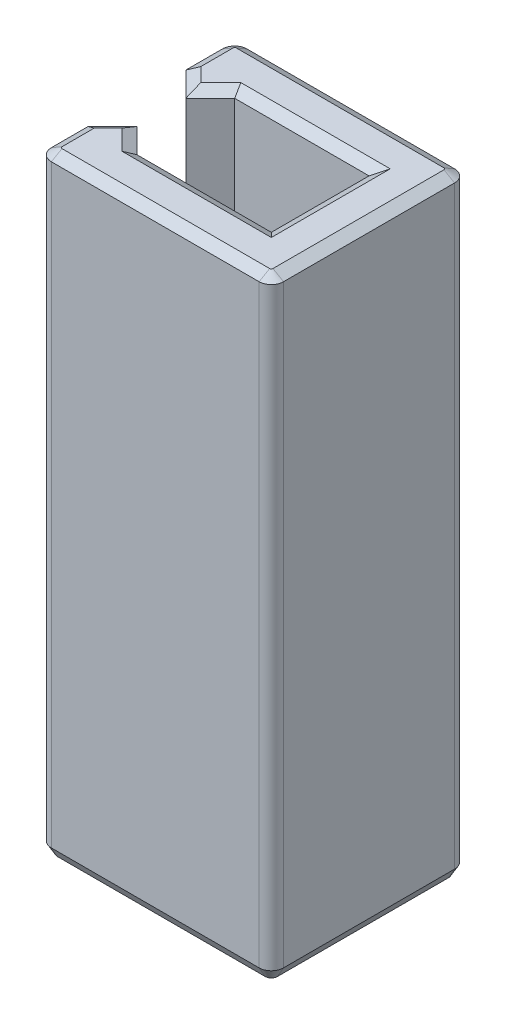
SolidWorks part; units mm, degrees
ref_plane "Alzado" through (0, 0, 0) normal (0, 0, 1) x (1, 0, 0)
ref_plane "Planta" through (0, 0, 0) normal (0, 1, 0) x (1, 0, 0)
ref_plane "Vista lateral" through (0, 0, 0) normal (1, 0, 0) x (0, 0, -1)
sketch "Croquis1" plane through (0, 0, 0) normal (0, 1, 0) x (1, 0, 0)
  line L0 (13.2185, 0) -> (-13.2185, 0) construction
  line L1 (-5.5, 4) -> (-7.5, 2)
  line L2 (8.5, -8) -> (-8.5, -8)
  line L3 (9.5, -7) -> (9.5, 7)
  line L4 (8.5, 8) -> (-8.5, 8)
  line L5 (-9.5, -7) -> (-9.5, -4)
  line L6 (9.5, -8) -> (-9.5, 8) construction
  line L7 (0, -13.2185) -> (0, 13.2185) construction
  line L8 (9.5, 8) -> (-9.5, -8) construction
  line L9 (-5.5, 4) -> (5.5, 4)
  line L10 (-9.5, 4) -> (-9.5, 7)
  line L11 (-5.5, -4) -> (5.5, -4)
  line L12 (5.5, 4) -> (5.5, -4)
  line L14 (-9.5, 4) -> (-7.5, 2)
  line L15 (-13.8316, -10.2338) -> (-13.8316, 16.2032) construction
  line L17 (-7.5, -2) -> (-9.5, -4)
  line L19 (-5.5, -4) -> (-7.5, -2)
  arc A0 (9.5, -7) -> (8.5, -8) centre (8.5, -7) cw
  arc A1 (-9.5, -7) -> (-8.5, -8) centre (-8.5, -7) ccw
  arc A2 (9.5, 7) -> (8.5, 8) centre (8.5, 7) ccw
  arc A3 (-8.5, 8) -> (-9.5, 7) centre (-8.5, 7) ccw
  point P0 (0, 0)
  point P1 (0, 0)
  point P11 (0, 0)
  point P16 (-9.5, 4)
  point P18 (5.5, 4)
  point P20 (-5.5, 4)
  point P27 (-5.5, 4)
  point P28 (-5.5, 4)
  point P29 (-9.5, -4)
  point P30 (-5.5, -4)
  point P31 (-7.5, -2)
  dimension "D11" = 1
  dimension "D1" = 19
  dimension "D2" = 16
  dimension "D3" = 8
  dimension "D4" = 11
  dimension "D5" = 4
  dimension "D6" = 2
  dimension "D7" = 2
  dimension "D8" = 0
  dimension "D9" = 2
  dimension "D10" = 2
extrude "Saliente-Extruir2" add sketch "Croquis1" along normal blind 50
sketch "Croquis3" plane through (9.5, 0, 0) normal (1, 0, 0) x (0, 0, -1)
  line L0 (0, 50) -> (0, 0) construction
  line L1 (-7, 50) -> (7, 50) construction
  line L2 (-3.3304, 19.5311) -> (-6.0665, 27.0487)
  line L3 (0, 25) -> (-8.4382, 48.1836) construction
  line L4 (-0.767, 18.3358) -> (4.8712, 20.3879)
  line L5 (-4.8712, 29.6121) -> (0.767, 31.6642)
  line L6 (6.0665, 22.9513) -> (3.3304, 30.4689)
  line L7 (-2.6463, 17.6517) -> (2.6463, 32.3483) construction
  line L8 (-6.7506, 28.9281) -> (6.7506, 21.0719) construction
  line L9 (-6.0665, 27.0487) -> (-4.8712, 29.6121)
  line L10 (3.3304, 30.4689) -> (0.767, 31.6642)
  line L11 (4.8712, 20.3879) -> (6.0665, 22.9513)
  line L12 (-3.3304, 19.5311) -> (-0.767, 18.3358)
  point P6 (0, 25)
  dimension "D1" = 10
  dimension "D2" = 12
sketch "Croquis4" plane through (0, 0, 8) normal (0, 0, 1) x (1, 0, 0)
  line L0 (0, 0) -> (0, 50) construction
  line L1 (-8.5, 50) -> (8.5, 50) construction
  circle A0 centre (0, 15) radius 3
  circle A1 centre (0, 35.64) radius 3
chamfer "Chaflán1" distance 0.5 angle 60 32 edges at (-6.5, 50, -3) (-8.5, 50, -3) (-9.5, 50, -5.5) (-9.2071, 50, -7.7071) (0, 50, -8) (9.2071, 50, -7.7071) (0, 50, -4) (5.5, 50, 0) (0, 50, 4) (-6.5, 50, 3) (-8.5, 50, 3) (-9.5, 50, 5.5) (-9.2071, 50, 7.7071) (0, 50, 8) (9.2071, 50, 7.7071) (9.5, 50, 0) (5.5, 0, 0) (0, 0, 4) (-6.5, 0, 3) (-8.5, 0, 3) (-9.5, 0, 5.5) (-9.2071, 0, 7.7071) (0, 0, 8) (9.2071, 0, 7.7071) (0, 0, -4) (-6.5, 0, -3) (-8.5, 0, -3) (-9.5, 0, -5.5) (-9.2071, 0, -7.7071) (0, 0, -8) (9.2071, 0, -7.7071) (9.5, 0, 0)
equation "\"..00mm\"=1"
